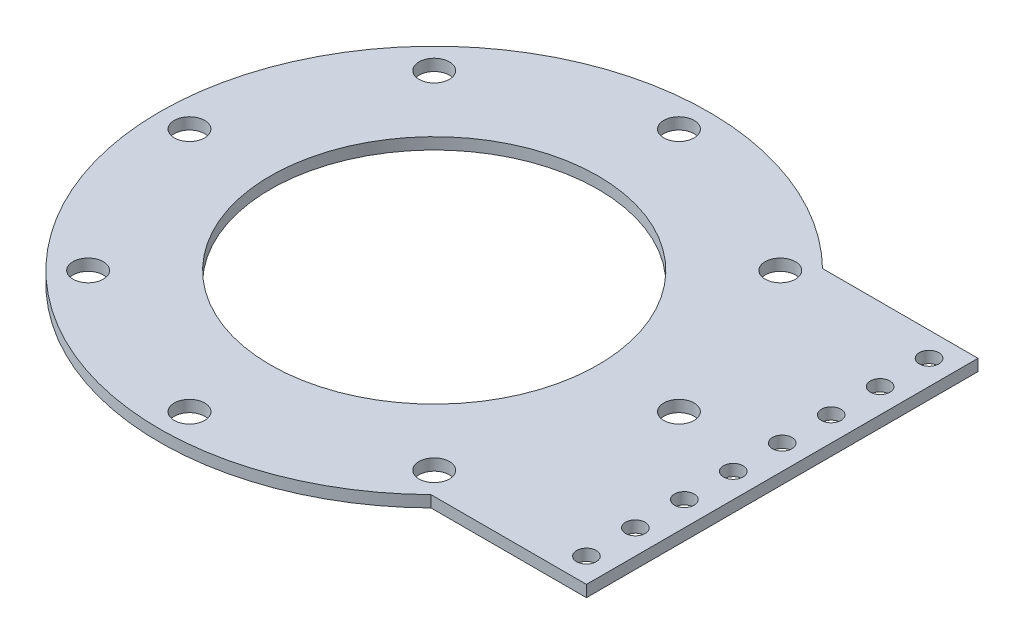
SolidWorks part; units mm, degrees
ref_plane "Front Plane" through (0, 0, 0) normal (0, 0, 1) x (1, 0, 0)
ref_plane "Top Plane" through (0, 0, 0) normal (0, 1, 0) x (1, 0, 0)
ref_plane "Right Plane" through (0, 0, 0) normal (1, 0, 0) x (0, 0, -1)
sketch "Sketch1" plane through (0, 0, 0) normal (0, 1, 0) x (1, 0, 0)
  line L0 (0, 0) -> (26.2305, 0) construction
  line L3 (0, 0) -> (0, -14.25) construction
  line L4 (9.9918, 10.16) -> (18.06, 10.16)
  line L7 (9.9918, 10.16) -> (9.9918, -10.16)
  line L8 (9.9918, -10.16) -> (18.06, -10.16)
  line L9 (18.06, 10.16) -> (18.06, -10.16)
  circle A0 centre (0, 0) radius 14.25
  circle A1 centre (0, 0) radius 8.5
  circle A7 centre (-8.9803, -8.9803) radius 0.7874
  circle A8 centre (-12.7, 0) radius 0.7874
  circle A9 centre (-8.9803, 8.9803) radius 0.7874
  circle A10 centre (0, 12.7) radius 0.7874
  circle A11 centre (8.9803, 8.9803) radius 0.7874
  circle A12 centre (12.7, 0) radius 0.7874
  circle A13 centre (8.9803, -8.9803) radius 0.7874
  circle A14 centre (0, -12.7) radius 0.7874
  circle A15 centre (16.79, 8.89) radius 0.508
  circle A16 centre (16.79, 6.35) radius 0.508
  circle A17 centre (16.79, 3.81) radius 0.508
  circle A18 centre (16.79, 1.27) radius 0.508
  circle A19 centre (16.79, -1.27) radius 0.508
  circle A20 centre (16.79, -3.81) radius 0.508
  circle A21 centre (16.79, -6.35) radius 0.508
  circle A22 centre (16.79, -8.89) radius 0.508
  circle A25 centre (16.79, -13.97) radius 0.508 [skipped]
  circle A26 centre (16.79, -11.43) radius 0.508 [skipped]
  point P8 (14.25, 0)
  point P38 (0, 0)
  point P61 (0, 0)
  dimension "D1" = 8
  dimension "D2" = 17
  dimension "D6" = 1.27
  dimension "D7" = 1.5748
  dimension "D3" = 8.89
  dimension "D10" = 1.016
  dimension "D4" = 2.54
  dimension "D5" = 1.27
  dimension "D8" = 12.7
  dimension "D9" = 10
extrude "Boss-Extrude1" add sketch "Sketch1" along normal blind 0.6
